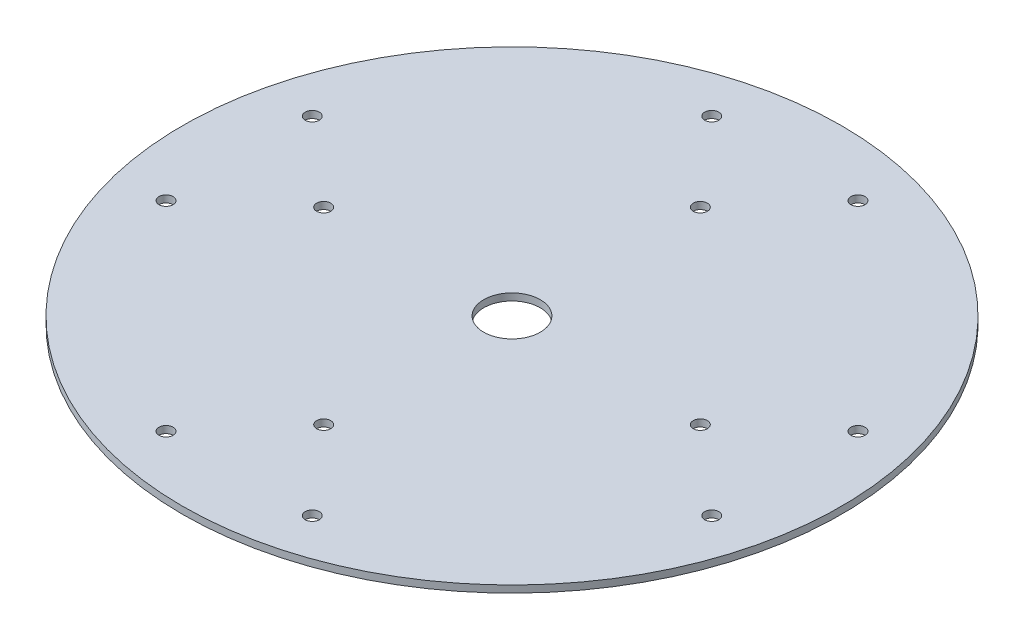
SolidWorks part; units mm, degrees
ref_plane "Front Plane" through (0, 0, 0) normal (0, 0, 1) x (1, 0, 0)
ref_plane "Top Plane" through (0, 0, 0) normal (0, 1, 0) x (1, 0, 0)
ref_plane "Right Plane" through (0, 0, 0) normal (1, 0, 0) x (0, 0, -1)
sketch "Sketch1" plane through (0, 0, 0) normal (0, 1, 0) x (1, 0, 0)
  line L0 (-15.5291, 57.9555) -> (0, 0) construction
  line L1 (0, 0) -> (15.5291, 57.9555) construction
  line L2 (0, 40) -> (0, 0) construction
  circle A0 centre (0, 0) radius 70
  circle A1 centre (0, 0) radius 6
  circle A2 centre (0, 40) radius 1.5
  circle A3 centre (-15.5291, 57.9555) radius 1.5
  circle A4 centre (15.5291, 57.9555) radius 1.5
  circle A5 centre (40, 0) radius 1.5
  circle A6 centre (57.9555, 15.5291) radius 1.5
  circle A7 centre (57.9555, -15.5291) radius 1.5
  circle A8 centre (0, -40) radius 1.5
  circle A9 centre (15.5291, -57.9555) radius 1.5
  circle A10 centre (-15.5291, -57.9555) radius 1.5
  circle A11 centre (-40, 0) radius 1.5
  circle A12 centre (-57.9555, -15.5291) radius 1.5
  circle A13 centre (-57.9555, 15.5291) radius 1.5
  point P31 (0, 0)
  dimension "D1" = 140
  dimension "D2" = 12
  dimension "D4" = 60
  dimension "D9" = 3
  dimension "D3" = 40
  dimension "D5" = 60
  dimension "D6" = 15
  dimension "D7" = 15
  dimension "D8" = 4
extrude "Boss-Extrude1" add sketch "Sketch1" along normal blind 1.5
